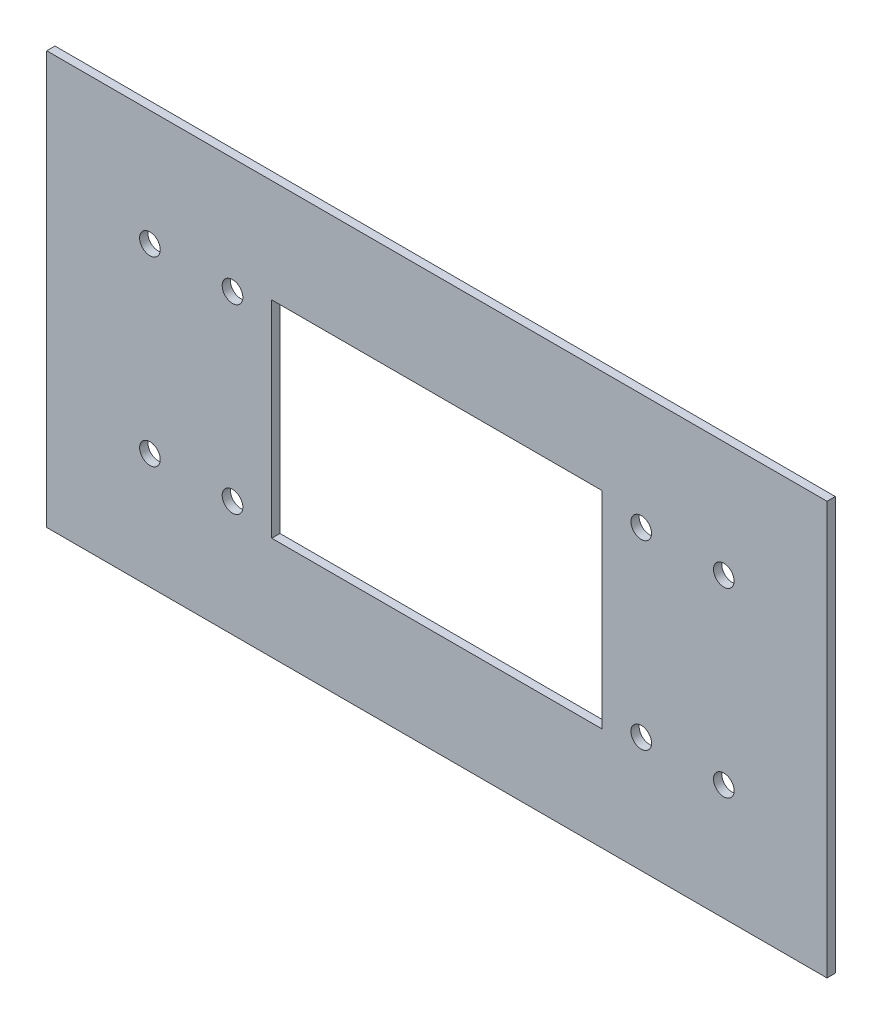
SolidWorks part; units mm, degrees
material "6063-T1"
ref_plane "Front Plane" through (0, 0, 0) normal (0, 0, 1) x (1, 0, 0)
ref_plane "Top Plane" through (0, 0, 0) normal (0, 1, 0) x (1, 0, 0)
ref_plane "Right Plane" through (0, 0, 0) normal (1, 0, 0) x (0, 0, -1)
sketch "Sketch1" plane through (0, 0, 0) normal (0, 0, 1) x (1, 0, 0)
  line L1 (0, 0) -> (189, 0)
  line L2 (0, 0) -> (0, 100)
  line L3 (0, 100) -> (189, 100)
  line L4 (189, 0) -> (189, 100)
  line L5 (54.5, 75) -> (134.5, 75)
  line L6 (54.5, 75) -> (54.5, 25)
  line L7 (54.5, 25) -> (134.5, 25)
  line L8 (134.5, 75) -> (134.5, 25)
  dimension "D1" = 189
  dimension "D2" = 100
  dimension "D3" = 25
  dimension "D4" = 25
  dimension "D5" = 80
  dimension "D6" = 54.5
extrude "Boss-Extrude1" add sketch "Sketch1" along normal blind 2
sketch "Sketch2" plane through (0, 0, 2) normal (0, 0, 1) x (1, 0, 0)
  line L0 (0, 100) -> (0, 0) construction
  line L1 (189, 0) -> (189, 100) construction
  line L2 (189, 100) -> (0, 100) construction
  line L3 (0, 0) -> (189, 0) construction
  circle A0 centre (25, 72) radius 2.5
  circle A1 centre (45, 72) radius 2.5
  circle A2 centre (25, 28) radius 2.5
  circle A3 centre (45, 28) radius 2.5
  circle A4 centre (144, 72) radius 2.5
  circle A5 centre (164, 72) radius 2.5
  circle A7 centre (144, 28) radius 2.5
  circle A8 centre (164, 28) radius 2.5
  dimension "D1" = 5
  dimension "D2" = 25
  dimension "D3" = 20
  dimension "D4" = 25
  dimension "D5" = 20
  dimension "D6" = 20
  dimension "D7" = 25
  dimension "D8" = 25
  dimension "D9" = 20
  dimension "D10" = 28
  dimension "D11" = 28
  dimension "D12" = 44
  dimension "D13" = 28
  dimension "D14" = 28
  dimension "D15" = 28
  dimension "D16" = 44
  dimension "D17" = 28
extrude "Cut-Extrude1" cut sketch "Sketch2" against normal blind 10
